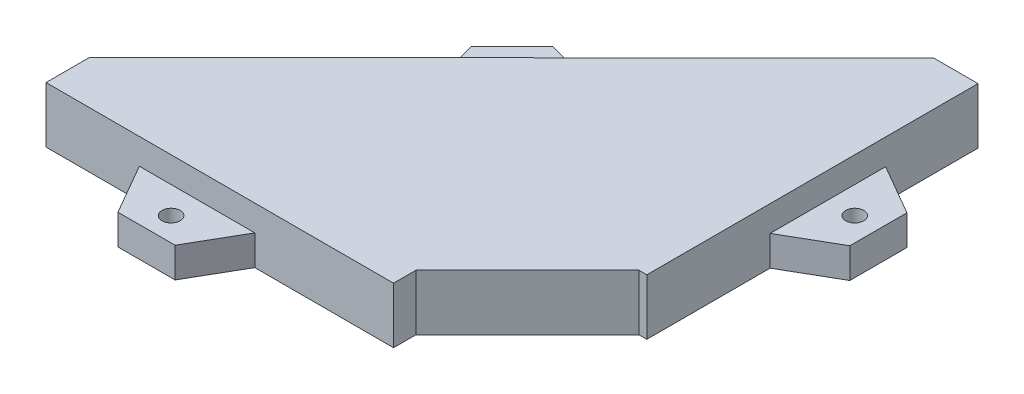
SolidWorks part; units mm, degrees
ref_plane "Front Plane" through (0, 0, 0) normal (0, 0, 1) x (1, 0, 0)
ref_plane "Top Plane" through (0, 0, 0) normal (0, 1, 0) x (1, 0, 0)
ref_plane "Right Plane" through (0, 0, 0) normal (1, 0, 0) x (0, 0, -1)
sketch "Sketch1" plane through (0, -14.2706, 0) normal (0, -1, 0) x (-1, 0, 0)
  line L0 (13.3152, -255.4666) -> (-78.534, -255.4666) construction
  line L1 (-78.534, -255.4666) -> (-78.534, -250.0918) construction
  line L2 (-78.534, -250.0918) -> (-104.2913, -224.3344) construction
  line L3 (-104.2913, -224.3344) -> (-106.2913, -224.3344) construction
  line L4 (-106.2913, -195.856) -> (-106.2913, -227.7092) construction
  line L5 (-141.0766, -224.3344) -> (-104.2913, -224.3344) construction
  line L6 (-106.2913, -224.3344) -> (-106.2913, -136.29) construction
  line L7 (-106.2913, -136.29) -> (13.3152, -255.4666) construction
  line L8 (-95.8045, -147.092) -> (2.5101, -245.0533)
  line L9 (2.5101, -255.2166) -> (-78.284, -255.2166)
  line L10 (-78.284, -255.2166) -> (-78.284, -249.9883)
  line L11 (-78.284, -249.9883) -> (-104.1878, -224.0844)
  line L12 (-104.1878, -224.0844) -> (-106.0413, -224.0844)
  line L13 (-106.0413, -224.0844) -> (-106.0413, -147.092)
  line L14 (-95.8045, -147.092) -> (-106.0413, -147.092)
  line L15 (-106.0413, -136.892) -> (-95.8045, -147.092) construction
  line L16 (-106.0413, -136.892) -> (12.7101, -255.2166) construction
  line L17 (-106.0413, -147.092) -> (-106.0413, -136.892) construction
  line L18 (-106.0413, -224.0844) -> (-106.0413, -136.892) construction
  line L19 (2.5101, -245.0533) -> (2.5101, -255.2166)
  line L20 (12.7101, -255.2166) -> (2.5101, -255.2166) construction
  line L21 (12.7101, -255.2166) -> (-78.284, -255.2166) construction
  line L22 (2.5101, -245.0533) -> (12.7101, -255.2166) construction
  dimension "D2" = 10.2
  dimension "D3" = 10.2
  dimension "D1" = 0.25
extrude "Boss-Extrude1" add sketch "Sketch1" against normal up to surface (13 mm away)
sketch "Sketch2" plane through (0, -14.2706, 0) normal (0, -1, 0) x (1, 0, 0)
  line L0 (-13.3152, 255.4666) -> (18.753, 255.4666) construction
  line L1 (18.753, 255.4666) -> (-2.6001, 255.4666) construction
  line L2 (18.753, 255.4666) -> (25.6812, 267.4666) construction
  line L3 (18.753, 255.4666) -> (25.6812, 267.4666) construction
  line L4 (25.6812, 267.4666) -> (39.5376, 267.4666) construction
  line L5 (39.5376, 267.4666) -> (46.4658, 255.4666) construction
  line L6 (46.4658, 255.4666) -> (78.534, 255.4666) construction
  line L7 (78.534, 255.4666) -> (78.534, 250.0918) construction
  line L8 (78.534, 250.0918) -> (104.2913, 224.3344) construction
  line L9 (104.2913, 224.3344) -> (106.2913, 224.3344) construction
  line L10 (106.2913, 195.856) -> (106.2913, 227.7092) construction
  line L11 (141.0766, 224.3344) -> (104.2913, 224.3344) construction
  line L12 (106.2913, 224.3344) -> (106.2913, 195.856) construction
  line L13 (106.2913, 195.856) -> (118.2913, 188.9278) construction
  line L14 (118.2913, 188.9278) -> (118.2913, 175.0714) construction
  line L15 (118.2913, 175.0714) -> (106.2913, 168.1432) construction
  line L16 (106.2913, 168.1432) -> (106.2913, 136.29) construction
  line L17 (106.2913, 136.29) -> (56.2961, 186.1055) construction
  line L18 (56.2961, 186.1055) -> (42.9044, 182.4914) construction
  line L19 (42.9044, 182.4914) -> (33.1064, 192.2894) construction
  line L20 (33.1064, 192.2894) -> (36.6853, 205.6459) construction
  line L21 (36.6853, 205.6459) -> (-13.3152, 255.4666) construction
  line L22 (37.2431, 205.7959) -> (-2.5101, 245.4062)
  line L23 (-2.5101, 254.9666) -> (19.0417, 254.9666)
  line L24 (19.0417, 254.9666) -> (25.9699, 266.9666)
  line L25 (25.9699, 266.9666) -> (39.2489, 266.9666)
  line L26 (39.2489, 266.9666) -> (46.1771, 254.9666)
  line L27 (46.1771, 254.9666) -> (78.034, 254.9666)
  line L28 (78.034, 254.9666) -> (78.034, 249.8847)
  line L29 (78.034, 249.8847) -> (104.0842, 223.8344)
  line L30 (104.0842, 223.8344) -> (105.7913, 223.8344)
  line L31 (105.7913, 223.8344) -> (105.7913, 195.5674)
  line L32 (105.7913, 195.5674) -> (117.7913, 188.6392)
  line L33 (117.7913, 188.6392) -> (117.7913, 175.3601)
  line L34 (117.7913, 175.3601) -> (105.7913, 168.4319)
  line L35 (105.7913, 168.4319) -> (105.7913, 147.092)
  line L36 (96.1587, 147.092) -> (56.4445, 186.6635)
  line L37 (56.4445, 186.6635) -> (43.0534, 183.0495)
  line L38 (43.0534, 183.0495) -> (33.6641, 192.4388)
  line L39 (33.6641, 192.4388) -> (37.2431, 205.7959)
  line L40 (-2.5101, 245.4062) -> (-2.5101, 254.9666)
  line L41 (-2.5101, 245.4062) -> (-12.105, 254.9666) construction
  line L42 (37.2431, 205.7959) -> (-12.105, 254.9666) construction
  line L43 (-12.105, 254.9666) -> (-2.5101, 254.9666) construction
  line L44 (-12.105, 254.9666) -> (19.0417, 254.9666) construction
  line L45 (-2.5101, 255.2166) -> (-2.5101, 245.0533) construction
  line L46 (96.1587, 147.092) -> (105.7913, 147.092)
  line L47 (95.8045, 147.092) -> (106.0413, 147.092) construction
  line L48 (105.7913, 147.092) -> (105.7913, 137.494) construction
  line L49 (105.7913, 168.4319) -> (105.7913, 137.494) construction
  line L50 (105.7913, 137.494) -> (96.1587, 147.092) construction
  line L51 (105.7913, 137.494) -> (56.4445, 186.6635) construction
  dimension "D1" = 0.5
extrude "Boss-Extrude2" add sketch "Sketch2" against normal up to surface (7 mm away)
sketch "Sketch3" plane through (0, -14.2706, 0) normal (0, -1, 0) x (1, 0, 0)
  circle A0 centre (42.248, 191.6331) radius 2.1
  circle A2 centre (32.8244, 261.4666) radius 2.1
  circle A3 centre (112.2913, 181.9996) radius 2.1
  dimension "D1" = 4.2
extrude "Cut-Extrude1" cut sketch "Sketch3" against normal through all
sketch "Sketch4" plane through (0, -14.2706, 0) normal (0, -1, 0) x (1, 0, 0)
  line L0 (39.2489, 266.9666) -> (25.9699, 266.9666) construction
  line L1 (36.8658, 261.4666) -> (34.8451, 264.9666)
  line L2 (34.8451, 264.9666) -> (30.8036, 264.9666)
  line L3 (30.8036, 264.9666) -> (28.7829, 261.4666)
  line L4 (28.7829, 261.4666) -> (30.8036, 257.9666)
  line L5 (30.8036, 257.9666) -> (34.8451, 257.9666)
  line L6 (34.8451, 257.9666) -> (36.8658, 261.4666)
  line L7 (46.1518, 192.6791) -> (43.294, 195.5368)
  line L8 (43.294, 195.5368) -> (39.3903, 194.4908)
  line L9 (39.3903, 194.4908) -> (38.3443, 190.5871)
  line L10 (38.3443, 190.5871) -> (41.202, 187.7293)
  line L11 (41.202, 187.7293) -> (45.1058, 188.7753)
  line L12 (45.1058, 188.7753) -> (46.1518, 192.6791)
  line L13 (108.7913, 184.0204) -> (108.7913, 179.9789)
  line L14 (108.7913, 179.9789) -> (112.2913, 177.9582)
  line L15 (112.2913, 177.9582) -> (115.7913, 179.9789)
  line L16 (115.7913, 179.9789) -> (115.7913, 184.0204)
  line L17 (115.7913, 184.0204) -> (112.2913, 186.0411)
  line L18 (112.2913, 186.0411) -> (108.7913, 184.0204)
  line L19 (33.6641, 192.4388) -> (43.0534, 183.0495) construction
  line L20 (117.7913, 175.3601) -> (117.7913, 188.6392) construction
  circle A0 centre (32.8244, 261.4666) radius 3.5 construction
  circle A1 centre (42.248, 191.6331) radius 3.5 construction
  circle A2 centre (112.2913, 181.9996) radius 3.5 construction
  dimension "D1" = 7
extrude "Cut-Extrude2" cut sketch "Sketch4" against normal blind 3.5
